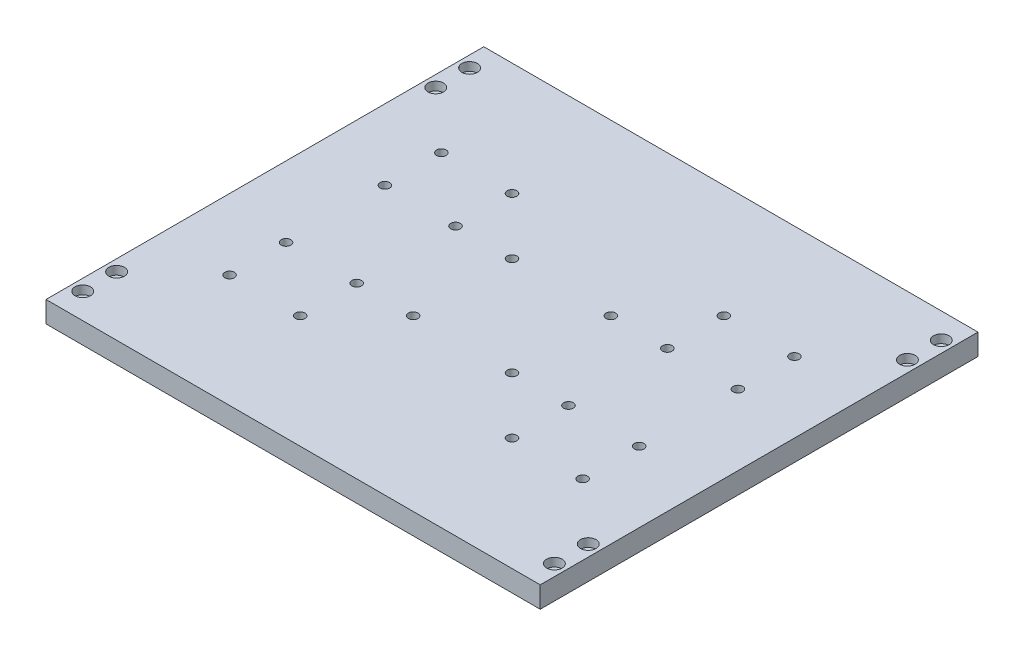
SolidWorks part; units mm, degrees
ref_plane "前视基准面" through (0, 0, 0) normal (0, 0, 1) x (1, 0, 0)
ref_plane "上视基准面" through (0, 0, 0) normal (0, 1, 0) x (1, 0, 0)
ref_plane "右视基准面" through (0, 0, 0) normal (1, 0, 0) x (0, 0, -1)
other "Configuration Table"
sketch "草图2" plane through (0, 0, 0) normal (0, 1, 0) x (1, 0, 0)
  line L1 (0, 0) -> (350, 0)
  line L2 (0, 0) -> (0, 310)
  line L3 (0, 310) -> (350, 310)
  line L4 (350, 0) -> (350, 310)
  dimension "D1" = 310
  dimension "D2" = 350
extrude "凸台-拉伸1" add sketch "草图2" along normal blind 15
sketch "草图5" plane through (0, 15, 0) normal (0, 1, 0) x (1, 0, 0)
  line L0 (0, 155) -> (388.1812, 155) construction
  line L1 (0, 310) -> (0, 0) construction
  line L2 (175, 310) -> (175, 45.3971) construction
  line L3 (350, 310) -> (0, 310) construction
sketch "草图3" plane through (0, 15, 0) normal (0, 1, 0) x (1, 0, 0)
  line L0 (388.1812, 155) -> (292.8744, 155) construction
  line L1 (0, 155) -> (388.1812, 155) construction
  line L2 (175, 45.3971) -> (175, -64.7432) construction
  circle A0 centre (342, 292) radius 3
  circle A1 centre (342, 268) radius 3
  circle A2 centre (342, 42) radius 3
  circle A3 centre (342, 18) radius 3
  circle A4 centre (8, 18) radius 3
  circle A5 centre (8, 42) radius 3
  circle A6 centre (8, 268) radius 3
  circle A7 centre (8, 292) radius 3
  dimension "D1" = 6
  dimension "D2" = 6
extrude "切除-拉伸1" cut sketch "草图3" against normal through all
sketch "草图4" plane through (0, 15, 0) normal (0, 1, 0) x (1, 0, 0)
  line L0 (268.7498, 155) -> (402.9482, 155) construction
  line L1 (0, 155) -> (388.1812, 155) construction
  line L2 (175, 86.4025) -> (175, -11.6227) construction
  line L3 (175, 310) -> (175, 45.3971) construction
  circle A0 centre (342, 292) radius 5.5
  circle A2 centre (342, 268) radius 5.5
  circle A3 centre (342, 42) radius 5.5
  circle A4 centre (342, 18) radius 5.5
  circle A5 centre (8, 18) radius 5.5
  circle A6 centre (8, 42) radius 5.5
  circle A7 centre (8, 268) radius 5.5
  circle A8 centre (8, 292) radius 5.5
  dimension "D1" = 11
  dimension "D2" = 11
extrude "切除-拉伸2" cut sketch "草图4" against normal blind 6
sketch "草图6" plane through (0, 15, 0) normal (0, 1, 0) x (1, 0, 0)
  line L0 (350, 310) -> (0, 310) construction
  line L1 (0, 310) -> (0, 0) construction
  line L3 (388.1812, 155) -> (243.4192, 155) construction
  line L4 (175, 190) -> (175, 232.9027) construction
  line L5 (175, 310) -> (175, 45.3971) construction
  circle A0 centre (50, 230) radius 4
  circle A11 centre (100, 230) radius 4
  circle A14 centre (50, 190) radius 4
  circle A18 centre (100, 190) radius 4
  circle A21 centre (250, 190) radius 4
  circle A22 centre (300, 190) radius 4
  circle A23 centre (150, 190) radius 4
  circle A24 centre (200, 190) radius 4
  circle A25 centre (250, 230) radius 4
  circle A26 centre (300, 230) radius 4
  circle A27 centre (150, 230) radius 4
  circle A28 centre (200, 230) radius 4
  circle A29 centre (300, 80) radius 4
  circle A30 centre (250, 80) radius 4
  circle A31 centre (300, 120) radius 4
  circle A32 centre (250, 120) radius 4
  circle A33 centre (50, 120) radius 4
  circle A34 centre (100, 120) radius 4
  circle A35 centre (100, 80) radius 4
  circle A36 centre (50, 80) radius 4
  circle A37 centre (140, 190) radius 4
  circle A38 centre (210, 190) radius 4
  circle A39 centre (210, 120) radius 4
  circle A40 centre (140, 120) radius 4
  dimension "D1" = 8
  dimension "D5" = 8
  dimension "D8" = 6
  dimension "D9" = 2
  dimension "D2" = 80
  dimension "D3" = 50
  dimension "D6" = 40
  dimension "D7" = 50
  dimension "D4" = 6
hole_wizard "M8 螺纹孔1" positions "3D草图1" profile "草图7" tap size "M8" standard "GB"
sketch3d "3D草图1"
  point P0 (50, 15, -230)
  point P3 (100, 15, -230)
  point P6 (50, 15, -190)
  point P9 (100, 15, -190)
  point P12 (140, 15, -190)
  point P15 (210, 15, -190)
  point P18 (250, 15, -230)
  point P21 (300, 15, -230)
  point P24 (300, 15, -190)
  point P27 (250, 15, -190)
  point P30 (50, 15, -120)
  point P33 (100, 15, -120)
  point P36 (140, 15, -120)
  point P39 (210, 15, -120)
  point P42 (250, 15, -120)
  point P45 (300, 15, -120)
  point P48 (300, 15, -80)
  point P51 (250, 15, -80)
  point P54 (100, 15, -80)
  point P57 (50, 15, -80)
sketch "草图7" plane through (50, 15, -230) normal (1, 0, 0) x (0, 0, 1)
  line L0 (0, 0) -> (0, 21.7929)
  line L1 (0, 21.7929) -> (3.4, 19.75)
  line L2 (3.4, 19.75) -> (3.4, 0)
  line L5 (3.4, 0) -> (0, 0)
  line L10 (0, 21.7929) -> (-3.4, 19.75) construction
  line L11 (0, -6.35) -> (0, 107.95) construction
  dimension "螺纹孔钻头直径" = 6.8
  dimension "螺纹孔钻头深度" = 19.75
  dimension "导头角度" = 118
cosmetic thread "孔螺蚊线1" parameters "D1"=16, "D2"=8
cosmetic thread "孔螺蚊线2" parameters "D1"=16, "D2"=8
cosmetic thread "孔螺蚊线3" parameters "D1"=16, "D2"=8
cosmetic thread "孔螺蚊线4" parameters "D1"=16, "D2"=8
cosmetic thread "孔螺蚊线5" parameters "D1"=16, "D2"=8
cosmetic thread "孔螺蚊线6" parameters "D1"=16, "D2"=8
cosmetic thread "孔螺蚊线7" parameters "D1"=16, "D2"=8
cosmetic thread "孔螺蚊线8" parameters "D1"=16, "D2"=8
cosmetic thread "孔螺蚊线9" parameters "D1"=16, "D2"=8
cosmetic thread "孔螺蚊线10" parameters "D1"=16, "D2"=8
cosmetic thread "孔螺蚊线11" parameters "D1"=16, "D2"=8
cosmetic thread "孔螺蚊线12" parameters "D1"=16, "D2"=8
cosmetic thread "孔螺蚊线13" parameters "D1"=16, "D2"=8
cosmetic thread "孔螺蚊线14" parameters "D1"=16, "D2"=8
cosmetic thread "孔螺蚊线15" parameters "D1"=16, "D2"=8
cosmetic thread "孔螺蚊线16" parameters "D1"=16, "D2"=8
cosmetic thread "孔螺蚊线17" parameters "D1"=16, "D2"=8
cosmetic thread "孔螺蚊线18" parameters "D1"=16, "D2"=8
cosmetic thread "孔螺蚊线19" parameters "D1"=16, "D2"=8
cosmetic thread "孔螺蚊线20" parameters "D1"=16, "D2"=8
